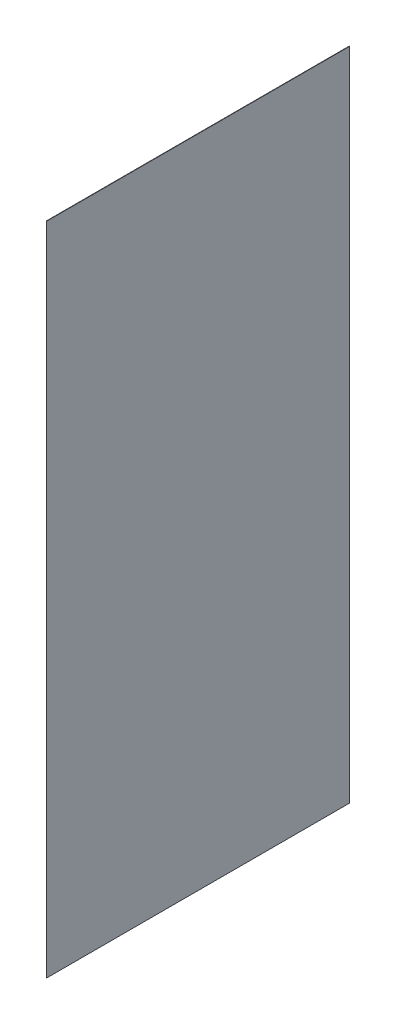
SolidWorks part; units mm, degrees
ref_plane "Front Plane" through (0, 0, 0) normal (0, 0, 1) x (1, 0, 0)
ref_plane "Top Plane" through (0, 0, 0) normal (0, 1, 0) x (1, 0, 0)
ref_plane "Right Plane" through (0, 0, 0) normal (1, 0, 0) x (0, 0, -1)
other "Configuration Table"
sketch "Sketch1" plane through (0, 0, 0) normal (0, 0, 1) x (1, 0, 0)
  line L1 (657.5, 241.5) -> (658.5, 241.5)
  line L2 (657.5, 241.5) -> (657.5, 1968.5)
  line L3 (657.5, 1968.5) -> (658.5, 1968.5)
  line L4 (658.5, 241.5) -> (658.5, 1968.5)
extrude "TOPPING_ic_yan_sag_1" add sketch "Sketch1" against normal blind 798.5 separate body
